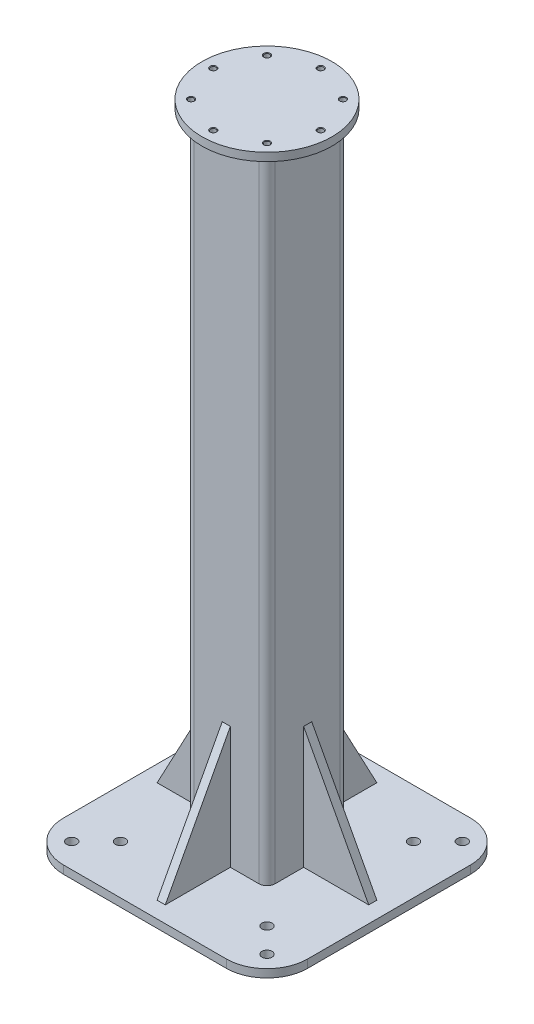
SolidWorks part; units mm, degrees
material "灰铸铁"
ref_plane "前视基准面" through (0, 0, 0) normal (0, 0, 1) x (1, 0, 0)
ref_plane "上视基准面" through (0, 0, 0) normal (0, 1, 0) x (1, 0, 0)
ref_plane "右视基准面" through (0, 0, 0) normal (1, 0, 0) x (0, 0, -1)
sketch "草图1" plane through (0, 0, 0) normal (0, 1, 0) x (1, 0, 0)
  line L1 (-150, -150) -> (150, -150)
  line L2 (-150, -150) -> (-150, 150)
  line L3 (-150, 150) -> (150, 150)
  line L4 (150, -150) -> (150, 150)
  line L5 (-150, -150) -> (150, 150) construction
  line L6 (-150, 150) -> (150, -150) construction
  point P0 (0, 0)
  dimension "D1" = 300
  dimension "D2" = 300
extrude "凸台-拉伸1" add sketch "草图1" along normal blind 10
sketch "草图2" plane through (0, 10, 0) normal (0, 1, 0) x (1, 0, 0)
  line L1 (-50, -50) -> (50, -50)
  line L2 (-50, -50) -> (-50, 50)
  line L3 (-50, 50) -> (50, 50)
  line L4 (50, -50) -> (50, 50)
  line L5 (-50, -50) -> (50, 50) construction
  line L6 (-50, 50) -> (50, -50) construction
  line L7 (-45, -45) -> (45, -45)
  line L8 (-45, -45) -> (-45, 45)
  line L9 (-45, 45) -> (45, 45)
  line L10 (45, -45) -> (45, 45)
  line L11 (-45, -45) -> (45, 45) construction
  line L12 (-45, 45) -> (45, -45) construction
  point P0 (0, 0)
  point P5 (0, 0)
  dimension "D1" = 100
  dimension "D2" = 90
extrude "凸台-拉伸2" add sketch "草图2" along normal blind 780
sketch "草图3" plane through (0, 790, 0) normal (0, 1, 0) x (1, 0, 0)
  circle A0 centre (0, 0) radius 80
  dimension "D1" = 160
extrude "凸台-拉伸4" add sketch "草图3" along normal blind 10
fillet "圆角3" radius 10 8 edges at (-45, 400, -45) (-50, 400, -50) (-50, 400, 50) (-45, 400, 45) (45, 400, 45) (50, 400, 50) (50, 400, -50) (45, 400, -45)
sketch "草图5" plane through (0, 800, 0) normal (0, 1, 0) x (1, 0, 0)
  circle A0 centre (0, 0) radius 66 construction
  point P3 (0, 66)
  point P4 (0, -66)
  point P5 (-66, 0)
  point P6 (66, 0)
  point P10 (46.669, 46.669)
  point P11 (-46.669, -46.669)
  point P12 (-46.669, 46.669)
  point P13 (46.669, -46.669)
  point P14 (0, 0)
  dimension "D1" = 132
  dimension "D2" = 2
hole_wizard "M8 螺纹孔1" positions "3D草图1" profile "草图6" tap size "M8" standard "ISO"
sketch3d "3D草图1"
  point P0 (-66, 800, 0)
  point P3 (-46.669, 800, -46.669)
  point P6 (0, 800, -66)
  point P9 (46.669, 800, -46.669)
  point P12 (66, 800, 0)
  point P15 (46.669, 800, 46.669)
  point P18 (0, 800, 66)
  point P21 (-46.669, 800, 46.669)
cosmetic thread "孔螺蚊线1" parameters "D1"=10, "D2"=8
cosmetic thread "孔螺蚊线2" parameters "D1"=10, "D2"=8
cosmetic thread "孔螺蚊线3" parameters "D1"=10, "D2"=8
cosmetic thread "孔螺蚊线4" parameters "D1"=10, "D2"=8
cosmetic thread "孔螺蚊线5" parameters "D1"=10, "D2"=8
cosmetic thread "孔螺蚊线6" parameters "D1"=10, "D2"=8
cosmetic thread "孔螺蚊线7" parameters "D1"=10, "D2"=8
cosmetic thread "孔螺蚊线8" parameters "D1"=10, "D2"=8
sketch "草图6" plane through (-66, 800, 0) normal (1, 0, 0) x (0, 0, 1)
  line L0 (0, 0) -> (0, 12.0429)
  line L1 (0, 12.0429) -> (3.4, 10)
  line L2 (3.4, 10) -> (3.4, 0.625)
  line L3 (3.4, 0.625) -> (4.025, 0)
  line L5 (4.025, 0) -> (0, 0)
  line L6 (-3.4, 0.625) -> (-4.025, 0) construction
  line L10 (0, 12.0429) -> (-3.4, 10) construction
  line L11 (0, -6.35) -> (0, 107.95) construction
  dimension "螺纹孔钻头直径" = 6.8
  dimension "螺纹孔钻头深度" = 10
  dimension "近端锥形沉头孔直径" = 8.05
  dimension "近端锥形沉头孔角度" = 90
  dimension "导头角度" = 118
sketch "草图7" plane through (0, 10, 0) normal (0, 1, 0) x (1, 0, 0)
  line L0 (150, -150) -> (150, 150) construction
  line L1 (150, 150) -> (-150, 150) construction
  line L2 (0, 0) -> (120, 120) construction
  circle A1 centre (120, 120) radius 6.25
  circle A2 centre (90, 90) radius 6.25
  dimension "D1" = 12.5
  dimension "D4" = 12.5
  dimension "D2" = 30
  dimension "D3" = 30
  dimension "D5" = 60
extrude "切除-拉伸1" cut sketch "草图7" against normal through all
mirror "镜向1" about plane through (0, 0, 0) normal (0, 0, 1) of "切除-拉伸1"
mirror "镜向2" about plane through (0, 0, 0) normal (1, 0, 0) of "镜向1", "切除-拉伸1"
sketch "草图8" plane through (0, 0, -50) normal (0, 0, -1) x (-1, 0, 0)
  line L0 (-5, 10) -> (5, 10)
  line L1 (-150, 10) -> (150, 10) construction
  line L2 (5, 10) -> (5, 160)
  line L3 (5, 160) -> (-5, 160)
  line L4 (-5, 160) -> (-5, 10)
  point P5 (0, 10)
  dimension "D1" = 10
  dimension "D2" = 150
extrude "凸台-拉伸5" add sketch "草图8" along normal blind 80
sketch "草图9" plane through (5, 0, 0) normal (1, 0, 0) x (0, 0, -1)
  line L0 (50, 160) -> (130, 10)
  line L1 (130, 10) -> (130, 160)
  line L2 (130, 160) -> (50, 160)
extrude "切除-拉伸2" cut sketch "草图9" against normal through all
pattern_circular "阵列(圆周)1" count 4 every 90 about axis through (0, 0, 0) along (0, 1, 0) of "切除-拉伸2", "凸台-拉伸5"
fillet "圆角4" radius 50 4 edges at (-150, 5, -150) (150, 5, -150) (150, 5, 150) (-150, 5, 150)
